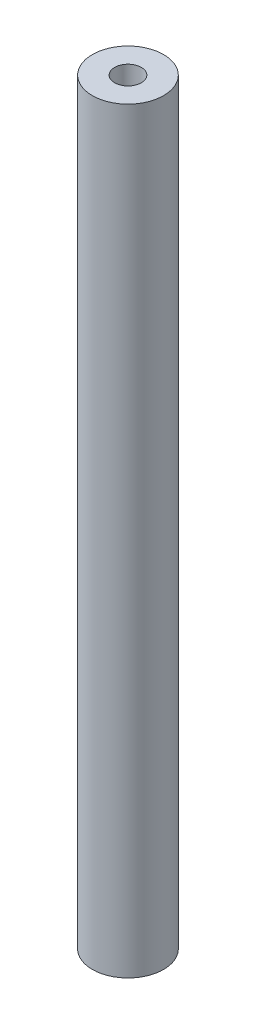
SolidWorks part; units mm, degrees
ref_plane "Front Plane" through (0, 0, 0) normal (0, 0, 1) x (1, 0, 0)
ref_plane "Top Plane" through (0, 0, 0) normal (0, 1, 0) x (1, 0, 0)
ref_plane "Right Plane" through (0, 0, 0) normal (1, 0, 0) x (0, 0, -1)
sketch "Sketch1" plane through (0, 0, 0) normal (0, 1, 0) x (1, 0, 0)
  circle A0 centre (0, 0) radius 4
  circle A1 centre (0, 0) radius 1.5
  dimension "D1" = 3
  dimension "D2" = 8
extrude "Boss-Extrude1" add sketch "Sketch1" along normal blind 85
